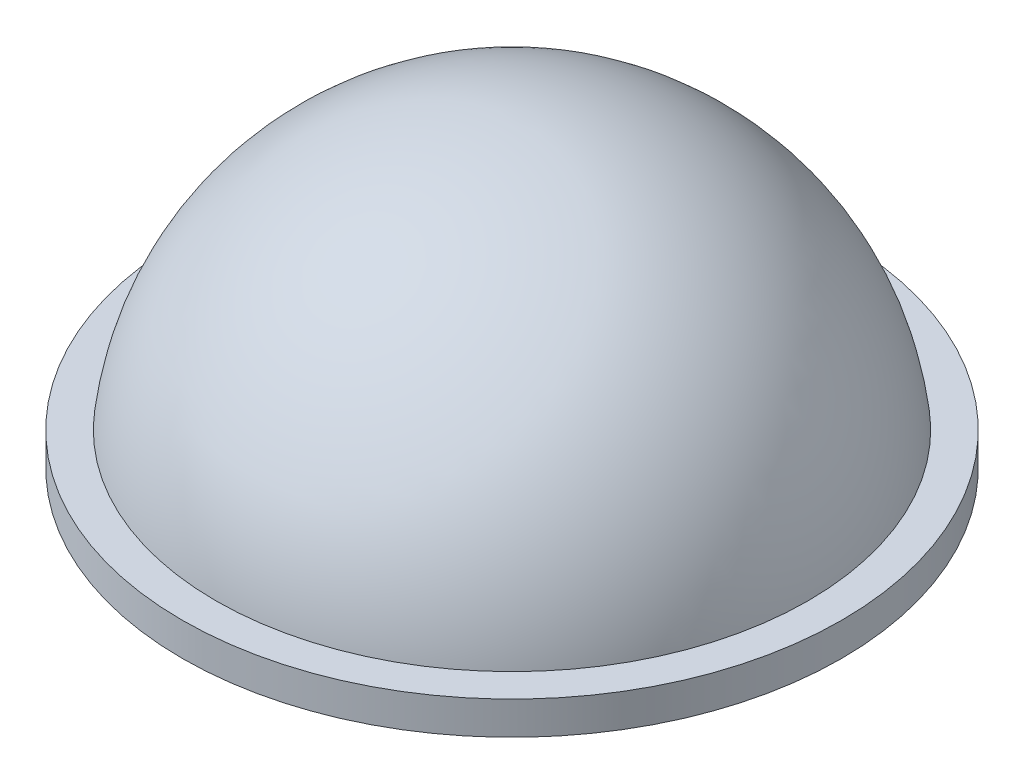
SolidWorks part; units mm, degrees
material "PC 高粘度"
ref_plane "前视基准面" through (0, 0, 0) normal (0, 0, 1) x (1, 0, 0)
ref_plane "上视基准面" through (0, 0, 0) normal (0, 1, 0) x (1, 0, 0)
ref_plane "右视基准面" through (0, 0, 0) normal (1, 0, 0) x (0, 0, -1)
other "Configuration Table"
sketch "草图1" plane through (0, 0, 0) normal (0, 0, 1) x (1, 0, 0)
  line L0 (0, 0) -> (-73.0503, 0) construction
  line L1 (-49.8, 0) -> (-40, 0)
  line L2 (-44.7214, 5) -> (-49.8, 5)
  line L3 (-49.8, 5) -> (-49.8, 0)
  line L4 (0, 45) -> (0, 40)
  line L5 (0, 45) -> (0, 0) construction
  arc A0 (0, 40) -> (-40, 0) centre (0, 0) ccw
  arc A1 (0, 45) -> (-44.7214, 5) centre (0, 0) ccw
  dimension "D1" = 80
  dimension "D2" = 90
  dimension "D3" = 49.8
  dimension "D4" = 5
revolve "旋转1" add sketch "草图1" angle 360 about L5
